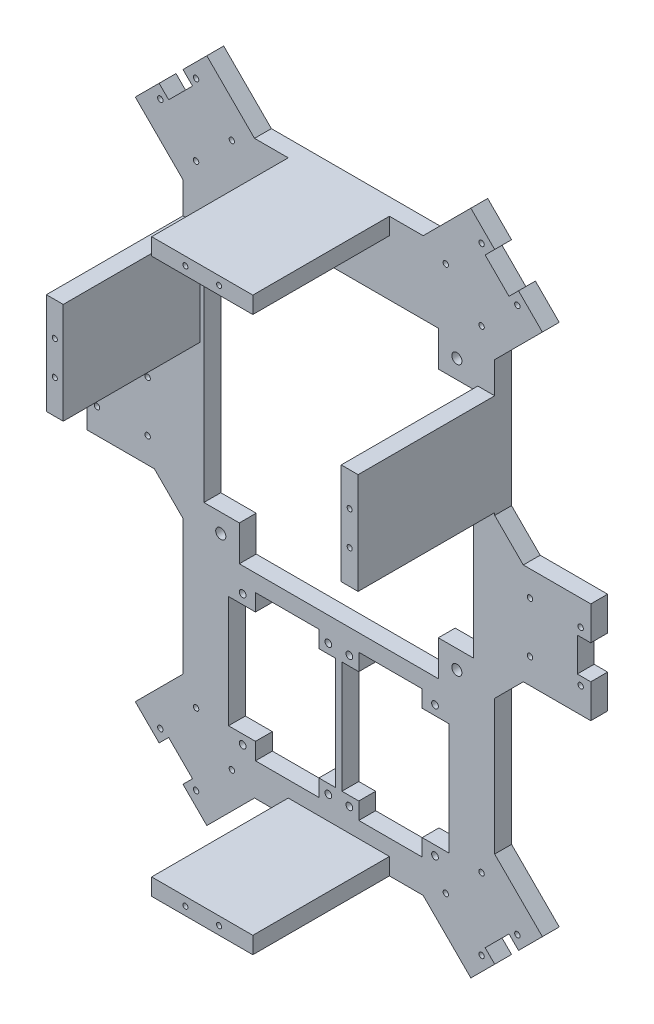
SolidWorks part; units mm, degrees
ref_plane "Płaszczyzna przednia" through (0, 0, 0) normal (0, 0, 1) x (1, 0, 0)
ref_plane "Płaszczyzna górna" through (0, 0, 0) normal (0, 1, 0) x (1, 0, 0)
ref_plane "Płaszczyzna prawa" through (0, 0, 0) normal (1, 0, 0) x (0, 0, -1)
sketch "Szkic1" plane through (0, 0, 0) normal (0, 0, 1) x (1, 0, 0)
  line L0 (0, 0) -> (-50, 0)
  line L1 (-50, 0) -> (-64.1421, 14.1421)
  line L2 (-64.1421, 14.1421) -> (-71.2132, 7.0711)
  line L3 (-71.2132, 7.0711) -> (-68.3848, 4.2426)
  line L4 (-68.3848, 4.2426) -> (-75.4558, -2.8284)
  line L5 (-75.4558, -2.8284) -> (-78.2843, 0)
  line L6 (-78.2843, 0) -> (-85.3553, -7.0711)
  line L7 (-85.3553, -7.0711) -> (-71.2132, -21.2132)
  line L8 (-71.2132, -21.2132) -> (-71.2132, -61.2132)
  line L9 (0, 0) -> (14.1421, 14.1421)
  line L10 (14.1421, 14.1421) -> (21.2132, 7.0711)
  line L11 (21.2132, 7.0711) -> (18.3848, 4.2426)
  line L12 (18.3848, 4.2426) -> (25.4558, -2.8284)
  line L13 (25.4558, -2.8284) -> (28.2843, 0)
  line L14 (28.2843, 0) -> (35.3553, -7.0711)
  line L15 (35.3553, -7.0711) -> (21.2132, -21.2132)
  line L16 (21.2132, -21.2132) -> (21.2132, -61.2132)
  line L17 (-71.2132, -61.2132) -> (-79.6985, -69.6985)
  line L18 (-79.6985, -69.6985) -> (-99.6985, -69.6985)
  line L19 (-99.6985, -69.6985) -> (-99.6985, -79.6985)
  line L20 (-99.6985, -79.6985) -> (-95.6985, -79.6985)
  line L21 (-95.6985, -79.6985) -> (-95.6985, -89.6985)
  line L22 (-95.6985, -89.6985) -> (-99.6985, -89.6985)
  line L23 (-99.6985, -89.6985) -> (-99.6985, -99.6985)
  line L24 (-99.6985, -99.6985) -> (-79.6985, -99.6985)
  line L25 (21.2132, -61.2132) -> (29.6985, -69.6985)
  line L26 (29.6985, -69.6985) -> (49.6985, -69.6985)
  line L27 (49.6985, -69.6985) -> (49.6985, -79.6985)
  line L28 (49.6985, -79.6985) -> (45.6985, -79.6985)
  line L29 (45.6985, -79.6985) -> (45.6985, -89.6985)
  line L30 (45.6985, -89.6985) -> (49.6985, -89.6985)
  line L31 (49.6985, -89.6985) -> (49.6985, -99.6985)
  line L32 (49.6985, -99.6985) -> (29.6985, -99.6985)
  line L33 (29.6985, -99.6985) -> (21.2132, -108.1838)
  line L34 (-79.6985, -99.6985) -> (-71.2132, -108.1838)
  line L35 (-71.2132, -108.1838) -> (-71.2132, -148.1838)
  line L36 (21.2132, -108.1838) -> (21.2132, -148.1838)
  line L37 (-71.2132, -148.1838) -> (-85.3553, -162.3259)
  line L38 (-85.3553, -162.3259) -> (-78.2843, -169.397)
  line L39 (-78.2843, -169.397) -> (-75.4558, -166.5685)
  line L40 (-75.4558, -166.5685) -> (-68.3848, -173.6396)
  line L41 (-68.3848, -173.6396) -> (-71.2132, -176.468)
  line L42 (-71.2132, -176.468) -> (-64.1421, -183.5391)
  line L43 (-64.1421, -183.5391) -> (-50, -169.397)
  line L44 (21.2132, -148.1838) -> (35.3553, -162.3259)
  line L45 (35.3553, -162.3259) -> (28.2843, -169.397)
  line L46 (28.2843, -169.397) -> (25.4558, -166.5685)
  line L47 (25.4558, -166.5685) -> (18.3848, -173.6396)
  line L48 (18.3848, -173.6396) -> (21.2132, -176.468)
  line L49 (21.2132, -176.468) -> (14.1421, -183.5391)
  line L50 (14.1421, -183.5391) -> (0, -169.397)
  line L51 (-50, -169.397) -> (0, -169.397)
  dimension "D1" = 225
  dimension "D2" = 225
  dimension "D3" = 20
  dimension "D4" = 20
  dimension "D5" = 10
  dimension "D6" = 4
  dimension "D7" = 50
  dimension "D8" = 10
  dimension "D9" = 10
  dimension "D10" = 20
  dimension "D11" = 4
  dimension "D12" = 10
  dimension "D13" = 4
  dimension "D14" = 10
  dimension "D15" = 4
  dimension "D16" = 10
  dimension "D17" = 20
  dimension "D18" = 225
  dimension "D19" = 40
  dimension "D20" = 12
  dimension "D21" = 20
  dimension "D22" = 10
  dimension "D23" = 4
  dimension "D24" = 10
  dimension "D25" = 4
  dimension "D26" = 10
  dimension "D27" = 20
  dimension "D29" = 12
  dimension "D30" = 20
  dimension "D31" = 10
  dimension "D32" = 4
  dimension "D33" = 10
  dimension "D34" = 4
  dimension "D35" = 10
  dimension "D36" = 20
  dimension "D37" = 12
  dimension "D38" = 12
  dimension "D39" = 40
  dimension "D40" = 40
  dimension "D41" = 20
  dimension "D42" = 10
  dimension "D43" = 4
  dimension "D44" = 10
  dimension "D45" = 4
  dimension "D46" = 10
  dimension "D47" = 20
  dimension "D48" = 20
  dimension "D49" = 10
  dimension "2" = 4
  dimension "D51" = 10
  dimension "D52" = 4
  dimension "D53" = 10
  dimension "D54" = 20
  dimension "D55" = 135
  dimension "D56" = 90
  dimension "D57" = 270
  dimension "D58" = 225
  dimension "D59" = 225
  dimension "D60" = 135
extrude "Dodanie-wyciągnięcie1" add sketch "Szkic1" along normal blind 5 contours L36 L44 L45 L46 L47 L48 L49 L50 L51 L43 L42 L41 L40 L39 L38 L37 L35 L34 L24 L23 L22 L21 L20 L19 L18 L17 L8 L7 L6 L5 L4 L3 L2 L1 L0 L9 L10 L11 L12 L13 L14 L15 L16 L25 L26 L27 L28 L29 L30 L31 L32 L33
sketch "Szkic3" plane through (0, 0, 0) normal (0, 0, 1) x (1, 0, 0)
  line L0 (49.6985, -69.6985) -> (49.6985, -79.6985) construction
  line L1 (29.6985, -69.6985) -> (49.6985, -69.6985) construction
  line L2 (35.3553, -162.3259) -> (28.2843, -169.397) construction
  line L3 (21.2132, -148.1838) -> (35.3553, -162.3259) construction
  line L4 (21.2132, -176.468) -> (14.1421, -183.5391) construction
  line L5 (14.1421, -183.5391) -> (0, -169.397) construction
  line L6 (-71.2132, -176.468) -> (-64.1421, -183.5391) construction
  line L7 (-85.3553, -162.3259) -> (-78.2843, -169.397) construction
  line L8 (-71.2132, -148.1838) -> (-85.3553, -162.3259) construction
  line L9 (-64.1421, -183.5391) -> (-50, -169.397) construction
  line L10 (35.3553, -7.0711) -> (21.2132, -21.2132) construction
  line L11 (28.2843, 0) -> (35.3553, -7.0711) construction
  line L12 (14.1421, 14.1421) -> (21.2132, 7.0711) construction
  line L13 (0, 0) -> (14.1421, 14.1421) construction
  line L14 (-85.3553, -7.0711) -> (-71.2132, -21.2132) construction
  line L15 (-50, 0) -> (-64.1421, 14.1421) construction
  line L16 (-78.2843, 0) -> (-85.3553, -7.0711) construction
  line L17 (-64.1421, 14.1421) -> (-71.2132, 7.0711) construction
  line L18 (49.6985, -99.6985) -> (29.6985, -99.6985) construction
  line L19 (49.6985, -89.6985) -> (49.6985, -99.6985) construction
  line L20 (-99.6985, -89.6985) -> (-99.6985, -99.6985) construction
  line L21 (-99.6985, -69.6985) -> (-99.6985, -79.6985) construction
  line L22 (-99.6985, -99.6985) -> (-79.6985, -99.6985) construction
  line L23 (-79.6985, -69.6985) -> (-99.6985, -69.6985) construction
  circle A0 centre (31.6985, -77.1985) radius 0.8
  circle A1 centre (46.6985, -77.1985) radius 0.8
  circle A2 centre (31.6985, -92.1985) radius 0.8
  circle A3 centre (46.6985, -92.1985) radius 0.8
  circle A4 centre (-81.6985, -77.1985) radius 0.8
  circle A5 centre (-96.6985, -77.1985) radius 0.8
  circle A6 centre (17.3241, -154.9013) radius 0.8
  circle A7 centre (27.9307, -165.5079) radius 0.8
  circle A8 centre (17.3241, -176.1145) radius 0.8
  circle A9 centre (6.7175, -165.5079) radius 0.8
  circle A10 centre (-67.3241, -154.9013) radius 0.8
  circle A11 centre (-77.9307, -165.5079) radius 0.8
  circle A12 centre (-67.3241, -176.1145) radius 0.8
  circle A13 centre (-56.7175, -165.5079) radius 0.8
  circle A14 centre (17.3241, 6.7175) radius 0.8
  circle A15 centre (27.9307, -3.8891) radius 0.8
  circle A16 centre (6.7175, -3.8891) radius 0.8
  circle A17 centre (17.3241, -14.4957) radius 0.8
  circle A18 centre (-67.3241, 6.7175) radius 0.8
  circle A19 centre (-56.7175, -3.8891) radius 0.8
  circle A20 centre (-77.9307, -3.8891) radius 0.8
  circle A21 centre (-67.3241, -14.4957) radius 0.8
  circle A22 centre (-96.6985, -92.1985) radius 0.8
  circle A23 centre (-81.6985, -92.1985) radius 0.8
  dimension "D1" = 1.6
  dimension "D4" = 1.6
  dimension "D6" = 1.6
  dimension "D7" = 1.6
  dimension "D10" = 1.6
  dimension "D13" = 1.6
  dimension "D16" = 1.6
  dimension "D17" = 1.6
  dimension "D22" = 1.6
  dimension "D23" = 1.6
  dimension "D24" = 1.6
  dimension "D25" = 1.6
  dimension "D34" = 1.6
  dimension "D35" = 1.6
  dimension "D36" = 1.6
  dimension "D37" = 1.6
  dimension "D46" = 1.6
  dimension "D47" = 1.6
  dimension "D48" = 1.6
  dimension "D49" = 1.6
  dimension "D61" = 1.6
  dimension "D62" = 1.6
  dimension "D63" = 1.6
  dimension "D64" = 1.6
  dimension "D2" = 18
  dimension "D3" = 7.5
  dimension "D5" = 15
  dimension "D8" = 15
  dimension "D9" = 15
  dimension "D11" = 18
  dimension "D12" = 7.5
  dimension "D14" = 15
  dimension "D15" = 7.5
  dimension "D18" = 18
  dimension "D19" = 7.5
  dimension "D20" = 7.5
  dimension "D21" = 15
  dimension "D26" = 15
  dimension "D27" = 15
  dimension "D28" = 18
  dimension "D29" = 18
  dimension "D30" = 7.5
  dimension "D31" = 7.5
  dimension "D32" = 7.5
  dimension "D33" = 7.5
  dimension "D38" = 15
  dimension "D39" = 15
  dimension "D40" = 7.5
  dimension "D41" = 7.5
  dimension "D42" = 18
  dimension "D43" = 18
  dimension "D44" = 7.5
  dimension "D45" = 7.5
  dimension "D50" = 7.5
  dimension "D51" = 7.5
  dimension "D52" = 7.5
  dimension "D53" = 7.5
  dimension "D54" = 18
  dimension "D55" = 18
  dimension "D56" = 15
  dimension "D57" = 15
  dimension "D58" = 7.5
  dimension "D59" = 7.5
  dimension "D60" = 18
  dimension "D65" = 18
  dimension "D66" = 18
  dimension "D67" = 15
  dimension "D68" = 15
  dimension "D69" = 7.5
  dimension "D70" = 7.5
  dimension "D71" = 7.5
  dimension "D72" = 7.5
  dimension "D73" = 15
extrude "Wytnij-wyciągnięcie3" cut sketch "Szkic3" against normal blind 4 and the other way blind 16
sketch "Szkic5" plane through (0, 0, 0) normal (0, 0, 1) x (1, 0, 0)
  line L0 (4.4968, -21.5) -> (-54.5032, -21.5)
  line L1 (-54.5032, -21.5) -> (-54.5032, -32)
  line L2 (-54.5032, -32) -> (-65.0032, -32)
  line L3 (-65.0032, -32) -> (-65.0032, -101)
  line L4 (-65.0032, -101) -> (-54.5032, -101)
  line L5 (-54.5032, -101) -> (-54.5032, -111.5)
  line L6 (-54.5032, -111.5) -> (4.4968, -111.5)
  line L7 (4.4968, -111.5) -> (4.4968, -101)
  line L8 (4.4968, -101) -> (14.9968, -101)
  line L9 (14.9968, -101) -> (14.9968, -32)
  line L10 (14.9968, -32) -> (4.4968, -32)
  line L11 (4.4968, -32) -> (4.4968, -21.5)
  line L12 (0, 0) -> (-50, 0) construction
  line L13 (-71.2132, -21.2132) -> (-71.2132, -61.2132) construction
  line L14 (21.2132, -21.2132) -> (21.2132, -61.2132) construction
  line L15 (-71.2132, -21.2132) -> (-71.2132, -61.2132) construction
  circle A0 centre (-60.0032, -26.5) radius 1.5
  circle A1 centre (9.9968, -26.5) radius 1.5
  circle A2 centre (9.9968, -106.5) radius 1.5
  circle A3 centre (-60.0032, -106.5) radius 1.5
  point P14 (-59.7532, -32)
  dimension "D16" = 3
  dimension "D19" = 3
  dimension "D22" = 3
  dimension "D25" = 3
  dimension "D1" = 21.5
  dimension "D2" = 69
  dimension "D3" = 10.5
  dimension "D4" = 10.5
  dimension "D5" = 90
  dimension "D6" = 10.5
  dimension "D7" = 59
  dimension "D8" = 6.21
  dimension "D9" = 10.5
  dimension "D10" = 10.5
  dimension "D11" = 59
  dimension "D12" = 10.5
  dimension "D13" = 10.5
  dimension "D14" = 10.5
  dimension "D15" = 80
  dimension "D17" = 5.5
  dimension "D18" = 5.5
  dimension "D20" = 5.5
  dimension "D21" = 5.5
  dimension "D23" = 5.5
  dimension "D24" = 5.5
  dimension "D26" = 5.5
  dimension "D27" = 5.5
  dimension "D28" = 5
  dimension "D29" = 5
  dimension "D30" = 5
  dimension "D31" = 5
  dimension "D32" = 5
  dimension "D33" = 5
  dimension "D34" = 5
  dimension "D35" = 5
  dimension "D36" = 6.2164
  dimension "D37" = 6.21
  dimension "D38" = 80
  dimension "D39" = 70
  dimension "D40" = 80
  dimension "D41" = 70
  dimension "D42" = 70
extrude "Wytnij-wyciągnięcie4" cut sketch "Szkic5" against normal blind 52 and the other way blind 26
sketch "Szkic6" plane through (0, 0, 5) normal (0, 0, 1) x (1, 0, 0)
  line L0 (-30.9132, -116.497) -> (-49.7132, -116.497)
  line L1 (-49.7132, -116.497) -> (-49.7132, -121.497)
  line L2 (-49.7132, -121.497) -> (-57.7132, -121.497)
  line L3 (-57.7132, -121.497) -> (-57.7132, -154.697)
  line L4 (-57.7132, -154.697) -> (-49.7132, -154.697)
  line L5 (-49.7132, -154.697) -> (-49.7132, -159.697)
  line L6 (-49.7132, -159.697) -> (-30.9132, -159.697)
  line L7 (-30.9132, -159.697) -> (-30.9132, -154.697)
  line L8 (-30.9132, -154.697) -> (-25.9132, -154.697)
  line L9 (-25.9132, -154.697) -> (-25.9132, -121.497)
  line L10 (-25.9132, -121.497) -> (-30.9132, -121.497)
  line L11 (-30.9132, -121.497) -> (-30.9132, -116.497)
  line L12 (-50, -169.397) -> (0, -169.397) construction
  line L13 (-0.2868, -121.497) -> (-0.2868, -116.497)
  line L14 (-71.2132, -108.1838) -> (-71.2132, -148.1838) construction
  line L16 (-19.0868, -116.497) -> (-19.0868, -121.497)
  line L17 (-19.0868, -121.497) -> (-24.0868, -121.497)
  line L18 (-24.0868, -121.497) -> (-24.0868, -154.697)
  line L19 (-24.0868, -154.697) -> (-19.0868, -154.697)
  line L20 (-19.0868, -154.697) -> (-19.0868, -159.697)
  line L21 (-19.0868, -159.697) -> (-0.2868, -159.697)
  line L22 (-0.2868, -159.697) -> (-0.2868, -154.697)
  line L23 (-0.2868, -154.697) -> (7.7132, -154.697)
  line L24 (7.7132, -154.697) -> (7.7132, -121.497)
  line L25 (7.7132, -121.497) -> (-0.2868, -121.497)
  line L26 (-19.0868, -116.497) -> (-0.2868, -116.497)
  line L27 (21.2132, -108.1838) -> (21.2132, -148.1838) construction
  line L28 (4.4968, -111.5) -> (-54.5032, -111.5) construction
  dimension "D1" = 43.2
  dimension "D2" = 9.7
  dimension "D3" = 5
  dimension "D4" = 8
  dimension "D5" = 18.8
  dimension "D6" = 8
  dimension "D7" = 5
  dimension "D8" = 5
  dimension "D9" = 5
  dimension "D10" = 5
  dimension "D11" = 13.5
  dimension "D12" = 33.2
  dimension "D13" = 9.7
  dimension "D14" = 43.2
  dimension "D15" = 5
  dimension "D16" = 33.2
  dimension "D17" = 8
  dimension "D18" = 8
  dimension "D19" = 18.8
  dimension "D20" = 5
  dimension "D21" = 5
  dimension "D22" = 5
  dimension "D23" = 5
  dimension "D24" = 13.5
  dimension "D25" = 1.8264
  dimension "D26" = 4.997
  dimension "D27" = 31.8
  dimension "D28" = 31.8
extrude "Wytnij-wyciągnięcie5" cut sketch "Szkic6" against normal blind 69 and the other way blind 31
sketch "Szkic7" plane through (0, 0, 5) normal (0, 0, 1) x (1, 0, 0)
  line L0 (-49.7132, -121.497) -> (-49.7132, -116.497) construction
  line L1 (-57.7132, -121.497) -> (-49.7132, -121.497) construction
  line L2 (-30.9132, -116.497) -> (-30.9132, -121.497) construction
  line L3 (-30.9132, -121.497) -> (-25.9132, -121.497) construction
  line L4 (-24.0868, -121.497) -> (-19.0868, -121.497) construction
  line L5 (-19.0868, -121.497) -> (-19.0868, -116.497) construction
  line L6 (-0.2868, -121.497) -> (7.7132, -121.497) construction
  line L7 (-0.2868, -116.497) -> (-0.2868, -121.497) construction
  line L8 (7.7132, -154.697) -> (-0.2868, -154.697) construction
  line L9 (-0.2868, -154.697) -> (-0.2868, -159.697) construction
  line L10 (-19.0868, -159.697) -> (-19.0868, -154.697) construction
  line L11 (-19.0868, -154.697) -> (-24.0868, -154.697) construction
  line L12 (-25.9132, -154.697) -> (-30.9132, -154.697) construction
  line L13 (-30.9132, -154.697) -> (-30.9132, -159.697) construction
  line L14 (-49.7132, -159.697) -> (-49.7132, -154.697) construction
  line L15 (-49.7132, -154.697) -> (-57.7132, -154.697) construction
  line L16 (-57.7132, -121.497) -> (-57.7132, -154.697) construction
  line L18 (-49.7132, -159.697) -> (-30.9132, -159.697) construction
  line L19 (-25.9132, -121.497) -> (-25.9132, -154.697) construction
  line L20 (-30.9132, -116.497) -> (-49.7132, -116.497) construction
  line L21 (-19.0868, -116.497) -> (-0.2868, -116.497) construction
  line L22 (-24.0868, -121.497) -> (-24.0868, -154.697) construction
  line L23 (7.7132, -121.497) -> (7.7132, -154.697) construction
  line L24 (-0.2868, -159.697) -> (-19.0868, -159.697) construction
  line L25 (7.7132, -154.697) -> (7.7132, -121.497) construction
  line L26 (-30.9132, -159.697) -> (-49.7132, -159.697) construction
  line L27 (-25.9132, -154.697) -> (-25.9132, -121.497) construction
  circle A0 centre (-53.5132, -118.697) radius 1
  circle A1 centre (-28.1132, -118.697) radius 1
  circle A2 centre (-21.8868, -118.697) radius 1
  circle A3 centre (3.5132, -118.697) radius 1
  circle A4 centre (3.5132, -157.497) radius 1
  circle A5 centre (-21.8868, -157.497) radius 1
  circle A6 centre (-28.1132, -157.497) radius 1
  circle A7 centre (-53.5132, -157.497) radius 1
  dimension "D1" = 2
  dimension "D4" = 2
  dimension "D5" = 2
  dimension "D10" = 2
  dimension "D13" = 2
  dimension "D16" = 2
  dimension "D17" = 2
  dimension "D22" = 2
  dimension "D2" = 3.8
  dimension "D3" = 2.8
  dimension "D6" = 2.8
  dimension "D7" = 2.8
  dimension "D8" = 2.8
  dimension "D9" = 2.8
  dimension "D11" = 2.8
  dimension "D12" = 3.8
  dimension "D14" = 2.8
  dimension "D15" = 3.8
  dimension "D18" = 2.8
  dimension "D19" = 2.8
  dimension "D20" = 2.8
  dimension "D21" = 2.8
  dimension "D23" = 3.8
  dimension "D24" = 2.8
  dimension "D25" = 4.2
  dimension "D26" = 4.2
  dimension "D27" = 2.2
  dimension "D28" = 2.2
  dimension "D29" = 2.2
  dimension "D30" = 2.2
  dimension "D31" = 2.2
  dimension "D32" = 2.2
  dimension "D33" = 4.2
  dimension "D34" = 2.2
  dimension "D35" = 2.2
  dimension "D36" = 2.2
  dimension "D37" = 4.2
  dimension "D38" = 2.2
  dimension "D39" = 2.2
  dimension "D40" = 2.2
extrude "Wytnij-wyciągnięcie6" cut sketch "Szkic7" against normal blind 83 and the other way blind 22
sketch "Szkic8" plane through (0, 0, 0) normal (0, 0, 1) x (1, 0, 0)
  line L0 (-40, 0) -> (-40, -5)
  line L1 (0, 0) -> (-50, 0) construction
  line L2 (-40, -5) -> (-10, -5)
  line L3 (-10, -5) -> (-10, 0)
  line L4 (-10, 0) -> (-40, 0)
  dimension "D1" = 10
  dimension "D2" = 30
  dimension "D3" = 10
  dimension "D4" = 5
extrude "Dodanie-wyciągnięcie2" add sketch "Szkic8" along normal blind 45.5 contours L2 L3 L4 L0
sketch "Szkic10" plane through (0, 0, 5) normal (0, 0, 1) x (1, 0, 0)
  line L0 (-40, -169.397) -> (-40, -164.397)
  line L1 (-50, -169.397) -> (0, -169.397) construction
  line L2 (-40, -164.397) -> (-10, -164.397)
  line L3 (-10, -164.397) -> (-10, -169.397)
  line L4 (-10, -169.397) -> (-40, -169.397)
  dimension "D1" = 30
  dimension "D2" = 5
  dimension "D3" = 10
  dimension "D4" = 10
extrude "Dodanie-wyciągnięcie3" add sketch "Szkic10" along normal blind 40.5
sketch "Szkic11" plane through (0, 0, 45.5) normal (0, 0, 1) x (1, 0, 0)
  line L0 (-10, 0) -> (-40, 0) construction
  line L2 (-40, -5) -> (-40, 0) construction
  line L3 (-10, -5) -> (-10, 0) construction
  circle A0 centre (-30, -2.5) radius 0.75
  circle A1 centre (-20, -2.5) radius 0.75
  dimension "D1" = 1.5
  dimension "D2" = 1.5
  dimension "D3" = 2.5
  dimension "D4" = 2.5
  dimension "D5" = 10
  dimension "D6" = 10
  dimension "D7" = 10
sketch "Szkic12" plane through (0, 0, 45.5) normal (0, 0, 1) x (1, 0, 0)
  line L0 (-10, -164.397) -> (-40, -164.397) construction
  line L1 (-10, -164.397) -> (-40, -164.397) construction
  line L3 (-40, -164.397) -> (-40, -169.397) construction
  line L4 (-10, -169.397) -> (-10, -164.397) construction
  circle A0 centre (-30, -166.897) radius 0.75
  circle A1 centre (-20, -166.897) radius 0.75
  dimension "D1" = 1.5
  dimension "D2" = 1.5
  dimension "D3" = 2.5
  dimension "D4" = 2.5
  dimension "D5" = 10
  dimension "D6" = 10
  dimension "D7" = 10
extrude "Wytnij-wyciągnięcie7" cut sketch "Szkic11" against normal blind 158 and the other way blind 112
extrude "Wytnij-wyciągnięcie8" cut sketch "Szkic12" against normal blind 402 and the other way blind 220
sketch "Szkic13" plane through (0, 0, 5) normal (0, 0, 1) x (1, 0, 0)
  line L0 (-71.2132, -30.5) -> (-66.2132, -30.5)
  line L1 (-71.2132, -21.2132) -> (-71.2132, -61.2132) construction
  line L2 (-66.2132, -30.5) -> (-66.2132, -60.5)
  line L3 (-66.2132, -60.5) -> (-71.2132, -60.5)
  line L4 (-71.2132, -60.5) -> (-71.2132, -30.5)
  line L5 (-65.0032, -32) -> (-54.5032, -32) construction
  line L6 (21.2132, -30.5) -> (16.2132, -30.5)
  line L7 (21.2132, -21.2132) -> (21.2132, -61.2132) construction
  line L8 (16.2132, -30.5) -> (16.2132, -60.5)
  line L9 (16.2132, -60.5) -> (21.2132, -60.5)
  line L10 (21.2132, -60.5) -> (21.2132, -30.5)
  line L11 (4.4968, -32) -> (14.9968, -32) construction
  dimension "D1" = 5
  dimension "D2" = 30
  dimension "D3" = 1.5
  dimension "D4" = 5
  dimension "D5" = 1.5
  dimension "D6" = 30
  dimension "D7" = 5
extrude "Dodanie-wyciągnięcie4" add sketch "Szkic13" along normal blind 40.5
sketch "Szkic14" plane through (0, 0, 0) normal (0, 0, 1) x (1, 0, 0)
  line L0 (-66.2132, -60.5) -> (-66.2132, -30.5) construction
  line L3 (16.2132, -30.5) -> (16.2132, -60.5) construction
  line L4 (16.2132, -30.5) -> (16.2132, -60.5) construction
  line L5 (0, 0) -> (-50, 0) construction
  circle A0 centre (-68.7132, -40.5) radius 0.75
  circle A1 centre (-68.7132, -50.5) radius 0.75
  circle A2 centre (18.7132, -40.5) radius 0.75
  circle A3 centre (18.7132, -50.5) radius 0.75
  dimension "D1" = 1.5
  dimension "D2" = 1.5
  dimension "D3" = 1.5
  dimension "D4" = 1.5
  dimension "D5" = 2.5
  dimension "D6" = 40.5
  dimension "D7" = 50.5
  dimension "D8" = 2.5
  dimension "D9" = 40.5
  dimension "D10" = 50.5
  dimension "D11" = 2.5
  dimension "D12" = 2.5
extrude "Wytnij-wyciągnięcie9" cut sketch "Szkic14" against normal blind 85 and the other way blind 48
